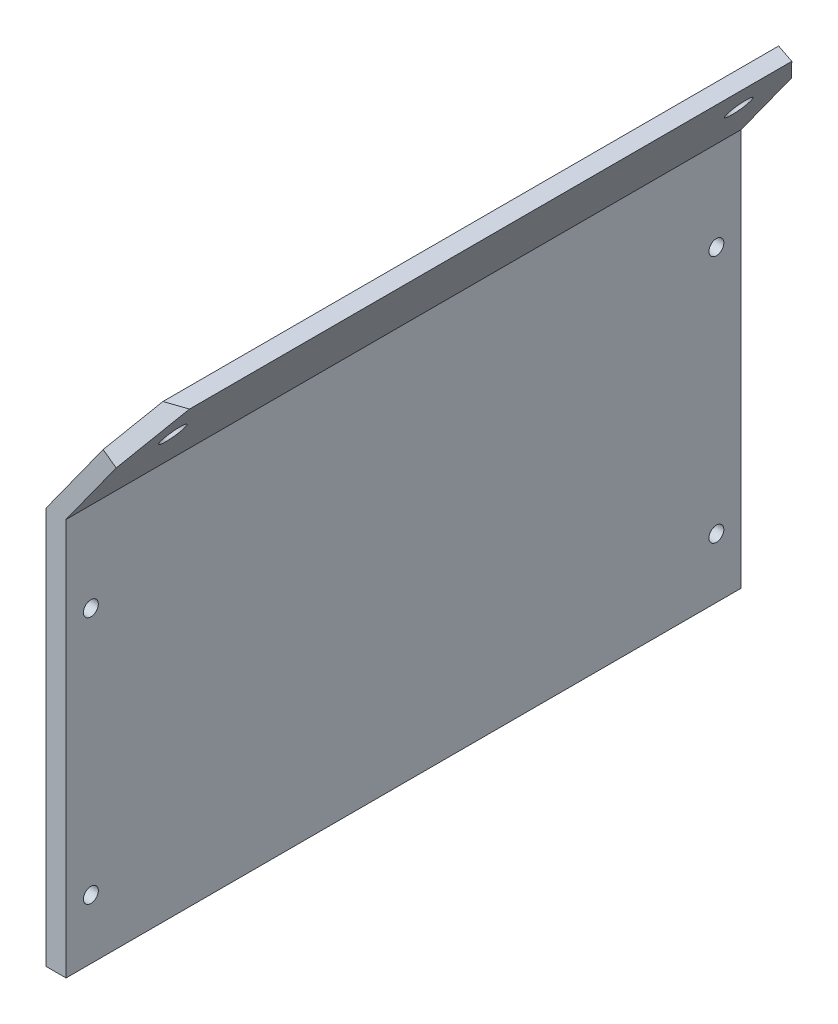
SolidWorks part; units mm, degrees
ref_plane "前视基准面" through (0, 0, 0) normal (0, 0, 1) x (1, 0, 0)
ref_plane "上视基准面" through (0, 0, 0) normal (0, 1, 0) x (1, 0, 0)
ref_plane "右视基准面" through (0, 0, 0) normal (1, 0, 0) x (0, 0, -1)
sketch "草图2" plane through (0, 0, 0) normal (0, 0, 1) x (1, 0, 0)
  line L0 (-38.8649, -21.5158) -> (-38.8649, 58.4842)
  line L1 (-38.8649, 58.4842) -> (-21.3357, 82.8302)
  line L2 (-21.3357, 82.8302) -> (-17.3357, 82.8302)
  line L3 (-17.3357, 82.8302) -> (-34.8649, 58.4842)
  line L4 (-34.8649, 58.4842) -> (-34.8649, -21.5158)
  line L5 (-34.8649, -21.5158) -> (-38.8649, -21.5158)
  dimension "D1" = 4
  dimension "D2" = 30
  dimension "D3" = 80
  dimension "D4" = 4
  dimension "D5" = 80
extrude "凸台-拉伸1" add sketch "草图2" along normal blind 136
sketch "草图3" plane through (-34.8649, 0, 0) normal (1, 0, 0) x (0, 0, -1)
  circle A0 centre (-131, 40.4842) radius 1.5
  circle A1 centre (-131, -9.5158) radius 1.5
  circle A2 centre (-5, 40.4842) radius 1.5
  circle A3 centre (-5, -9.5158) radius 1.5
  dimension "D1" = 3
  dimension "D2" = 3
  dimension "D3" = 3
  dimension "D4" = 3
extrude "切除-拉伸1" cut sketch "草图3" against normal blind 136
sketch "草图4" plane through (-50.6938, 36.4995, 0) normal (0.8115, -0.5843, 0) x (0, 0, -1)
  circle A0 centre (-125, 45.0902) radius 2.5
  circle A1 centre (-11, 45.0902) radius 2.5
  dimension "D4" = 5
  dimension "D5" = 5
extrude "切除-拉伸2" cut sketch "草图4" against normal blind 136
sketch "草图5" plane through (-50.6938, 36.4995, 0) normal (0.8115, -0.5843, 0) x (0, 0, -1)
  line L0 (-136, 44.3783) -> (-136, 60.4224)
  line L1 (-136, 27.0902) -> (-136, 57.0902) construction
  line L2 (-7.3392, 57.0902) -> (0, 57.0902)
  line L3 (0, 27.0902) -> (0, 57.0902) construction
  line L4 (-136, 44.3783) -> (-128.6608, 57.0902)
  line L5 (-136, 57.0902) -> (0, 57.0902) construction
  line L6 (0, 44.3783) -> (-7.3392, 57.0902)
  line L7 (-136, 60.4224) -> (-128.6608, 57.0902)
  line L8 (0, 57.0902) -> (0, 44.3783)
  dimension "D3" = 30
extrude "切除-拉伸3" cut sketch "草图5" against normal blind 136
